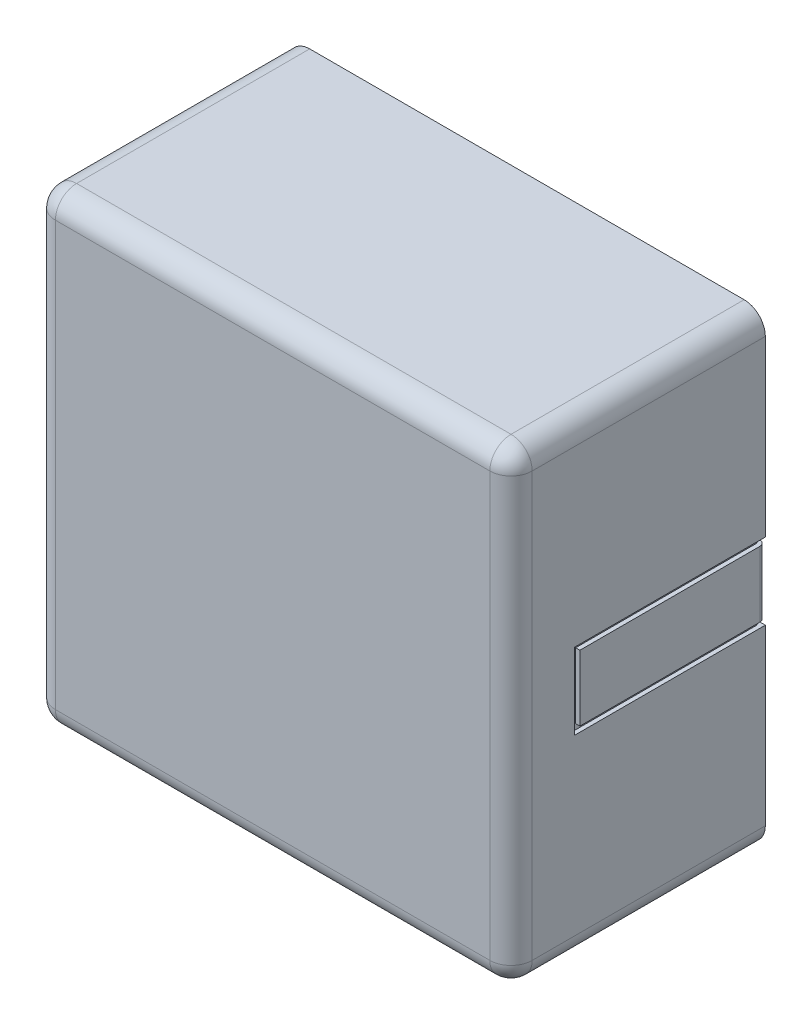
SolidWorks part; units mm, degrees
ref_plane "Front Plane" through (0, 0, 0) normal (0, 0, 1) x (1, 0, 0)
ref_plane "Top Plane" through (0, 0, 0) normal (0, 1, 0) x (1, 0, 0)
ref_plane "Right Plane" through (0, 0, 0) normal (1, 0, 0) x (0, 0, -1)
sketch "Sketch2" plane through (0, 0, 0) normal (0, 0, 1) x (1, 0, 0)
  line L1 (-11.25, 11) -> (11.25, 11)
  line L2 (-11.25, 11) -> (-11.25, -11)
  line L3 (-11.25, -11) -> (11.25, -11)
  line L4 (11.25, 11) -> (11.25, -11)
  point P4 (11.25, 0)
  point P6 (0, 11)
  dimension "D1" = 22.5
  dimension "D2" = 22
extrude "Boss-Extrude1" add sketch "Sketch2" along normal blind 12
sketch "Sketch3" plane through (0, 0, 0) normal (0, 0, -1) x (-1, 0, 0)
  line L0 (-11.25, -11) -> (-11.25, 11) construction
  line L1 (-11.25, -1.8) -> (-5.7, -1.8)
  line L2 (-11.25, -1.8) -> (-11.25, 1.8)
  line L3 (-11.25, 1.8) -> (-5.7, 1.8)
  line L4 (-5.7, -1.8) -> (-5.7, 1.8)
  line L5 (11.25, 11) -> (11.25, -11) construction
  line L6 (5.7, 1.8) -> (11.25, 1.8)
  line L7 (5.7, 1.8) -> (5.7, -1.8)
  line L8 (5.7, -1.8) -> (11.25, -1.8)
  line L9 (11.25, 1.8) -> (11.25, -1.8)
  point P12 (-11.25, 0)
  point P13 (-11.25, 0)
  dimension "D1" = 3.6
  dimension "D2" = 5.55
extrude "Cut-Extrude1" cut sketch "Sketch3" against normal blind 0.2
sketch "Sketch4" plane through (11.25, 0, 0) normal (1, 0, 0) x (0, 0, -1)
  line L0 (0, 1.8) -> (0, 11) construction
  line L1 (-0.2, -1.8) -> (-9, -1.8)
  line L2 (-0.2, -1.8) -> (-0.2, 1.8)
  line L3 (-0.2, 1.8) -> (-9, 1.8)
  line L4 (-9, -1.8) -> (-9, 1.8)
  dimension "D1" = 9
extrude "Cut-Extrude2" cut sketch "Sketch4" against normal blind 0.2
mirror "Mirror1" about plane through (0, 0, 0) normal (1, 0, 0) of "Cut-Extrude2"
fillet "Fillet1" radius 1 8 edges at (0, 11, 12) (11.25, 0, 12) (0, -11, 12) (-11.25, 0, 12) (11.25, -11, 6) (-11.25, -11, 6) (-11.25, 11, 6) (11.25, 11, 6)
sketch "Sketch5" plane through (0, 0, 0) normal (0, 0, -1) x (-1, 0, 0)
  line L0 (-11.25, 1.8) -> (-11.25, -1.8) construction
  line L1 (-5.95, 1.55) -> (-11.25, 1.55)
  line L2 (-5.95, 1.55) -> (-5.95, -1.55)
  line L3 (-5.95, -1.55) -> (-11.25, -1.55)
  line L4 (-11.25, 1.55) -> (-11.25, -1.55)
  line L5 (5.95, 1.55) -> (11.25, 1.55)
  line L6 (5.95, 1.55) -> (5.95, -1.55)
  line L7 (5.95, -1.55) -> (11.25, -1.55)
  line L8 (11.25, 1.55) -> (11.25, -1.55)
  line L9 (-5.7, 1.8) -> (-11.25, 1.8) construction
  line L11 (-5.7, -1.8) -> (-5.7, 1.8) construction
  line L12 (-11.05, -1.8) -> (-5.7, -1.8) construction
  line L13 (11.25, 1.8) -> (11.25, -1.8) construction
  dimension "D1" = 0.25
  dimension "D2" = 0.25
  dimension "D3" = 0.25
extrude "Boss-Extrude2" add sketch "Sketch5" against normal blind 8.75
fillet "Fillet2" radius 0.25 2 edges at (-11.25, 0, 0) (11.25, 0, 0)
